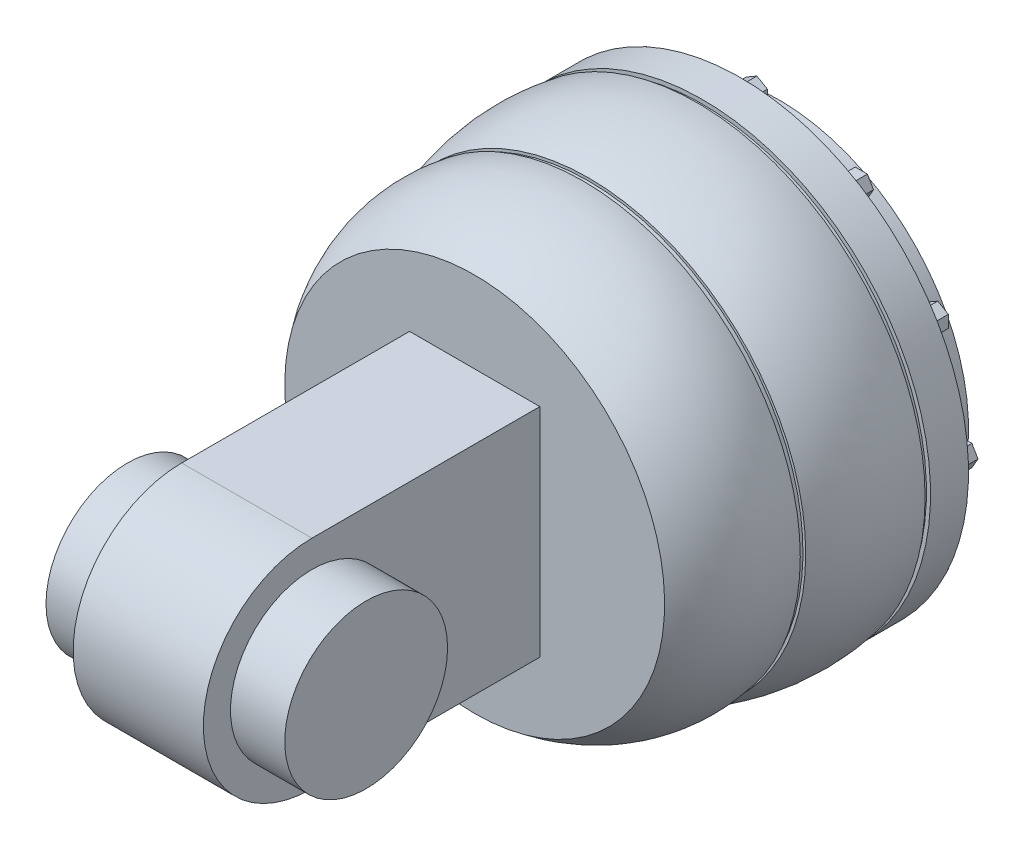
SolidWorks part; units mm, degrees
ref_plane "Front Plane" through (0, 0, 0) normal (1, 0, 0) x (0, 1, 0)
ref_plane "Top Plane" through (0, 0, 0) normal (0, 0, 1) x (0, 1, 0)
ref_plane "Right Plane" through (0, 0, 0) normal (0, 1, 0) x (-1, 0, 0)
sketch "Sketch1" plane through (0, 0, 0) normal (1, 0, 0) x (0, 1, 0)
  line L0 (-35, 0) -> (0, 0)
  line L1 (0, 0) -> (0, -20)
  line L2 (0, -20) -> (-40, -20)
  arc A0 (-40, -20) -> (-35, 0) centre (-15.404, -15.524) cw
  dimension "D4" = 25
  dimension "D1" = 35
  dimension "D2" = 20
  dimension "D3" = 40
revolve "Revolve1" add sketch "Sketch1" angle 360 about L1
sketch "Sketch2" plane through (0, 0, -20) normal (0, 0, -1) x (1, 0, 0)
  circle A0 centre (0, 0) radius 39.5
  dimension "D1" = 79
extrude "Boss-Extrude1" add sketch "Sketch2" along normal blind 1
sketch "Sketch3" plane through (0, 0, 0) normal (0, 1, 0) x (-1, 0, 0)
  line L0 (0, -21) -> (0, -41)
  line L1 (-39.5, -21) -> (39.5, -21) construction
  line L2 (0, -41) -> (-42, -41)
  line L3 (0, -21) -> (-40, -21)
  arc A0 (-42, -41) -> (-40, -21) centre (-5.5677, -34.5432) cw
  dimension "D4" = 37
  dimension "D1" = 40
  dimension "D2" = 20
  dimension "D3" = 42
revolve "Revolve2" add sketch "Sketch3" angle 360 about L0
sketch "Sketch4" plane through (0, 0, -41) normal (0, 0, -1) x (1, 0, 0)
  circle A0 centre (0, 0) radius 41.25
  dimension "D1" = 82.5
extrude "Boss-Extrude2" add sketch "Sketch4" along normal blind 1
sketch "Sketch5" plane through (0, 0, -42) normal (0, 0, -1) x (1, 0, 0)
  circle A0 centre (0, 0) radius 42
extrude "Boss-Extrude3" add sketch "Sketch5" along normal blind 7
sketch "Sketch6" plane through (0, 0, -49) normal (0, 0, -1) x (1, 0, 0)
  circle A0 centre (0, 0) radius 35
extrude "Boss-Extrude4" add sketch "Sketch6" along normal blind 7
sketch "Sketch7" plane through (0, 0, -49) normal (0, 0, -1) x (1, 0, 0)
  line L0 (36.25, 0) -> (36.5514, 0)
  line L1 (39.0476, 0.9486) -> (37.9524, 0.9486)
  line L2 (40.75, 0) -> (39.625, 1.9486)
  line L3 (39.625, 1.9486) -> (37.375, 1.9486)
  line L4 (37.375, 1.9486) -> (36.25, 0)
  line L5 (36.25, 0) -> (37.375, -1.9486)
  line L6 (37.375, -1.9486) -> (39.625, -1.9486)
  line L7 (39.625, -1.9486) -> (40.75, 0)
  line L8 (37.9524, 0.9486) -> (37.4047, 0)
  line L9 (37.4047, 0) -> (37.9524, -0.9486)
  line L10 (37.9524, -0.9486) -> (39.0476, -0.9486)
  line L11 (39.0476, -0.9486) -> (39.5953, 0)
  line L12 (39.5953, 0) -> (39.0476, 0.9486)
  line L13 (40.4486, 0) -> (40.75, 0)
  circle A3 centre (38.5, 0) radius 1.9486 construction
  dimension "D1" = 4.5
  dimension "D2" = 1
extrude "Boss-Extrude5" add sketch "Sketch7" along normal blind 3
pattern_circular "CirPattern1" count 12 over 360 about axis through (0, 0, 0) along (0, 0, 1) of "Boss-Extrude5"
sketch "Sketch8" plane through (0, 0, -56) normal (0, 0, -1) x (1, 0, 0)
  circle A0 centre (0, 0) radius 15
  dimension "D1" = 30
extrude "Boss-Extrude6" add sketch "Sketch8" along normal blind 10
sketch "Sketch9" plane through (0, 0, 0) normal (0, 0, 1) x (1, 0, 0)
  line L1 (-12, -20) -> (12, -20)
  line L2 (-12, -20) -> (-12, 20)
  line L3 (-12, 20) -> (12, 20)
  line L4 (12, -20) -> (12, 20)
  line L5 (-12, -20) -> (12, 20) construction
  line L6 (-12, 20) -> (12, -20) construction
  point P0 (0, 0)
extrude "Boss-Extrude7" add sketch "Sketch9" along normal blind 42
sketch "Sketch10" plane through (12, 0, 0) normal (1, 0, 0) x (0, 1, 0)
  line L0 (-20, 42) -> (20, 42) construction
  line L1 (-20, 42) -> (20, 42)
  arc A0 (20, 42) -> (-20, 42) centre (0, 42) ccw
extrude "Boss-Extrude8" add sketch "Sketch10" against normal blind 24 separate body
sketch "Sketch11" plane through (12, 0, 0) normal (1, 0, 0) x (0, 1, 0)
  line L0 (-20, 42) -> (20, 42) construction
  circle A0 centre (0, 42) radius 15
extrude "Boss-Extrude9" add sketch "Sketch11" along normal blind 10
sketch "Sketch12" plane through (-12, 0, 0) normal (-1, 0, 0) x (0, -1, 0)
  circle A0 centre (0, 42) radius 15
extrude "Boss-Extrude10" add sketch "Sketch12" along normal blind 10
ref_point "Point1"
ref_point "Point2"
